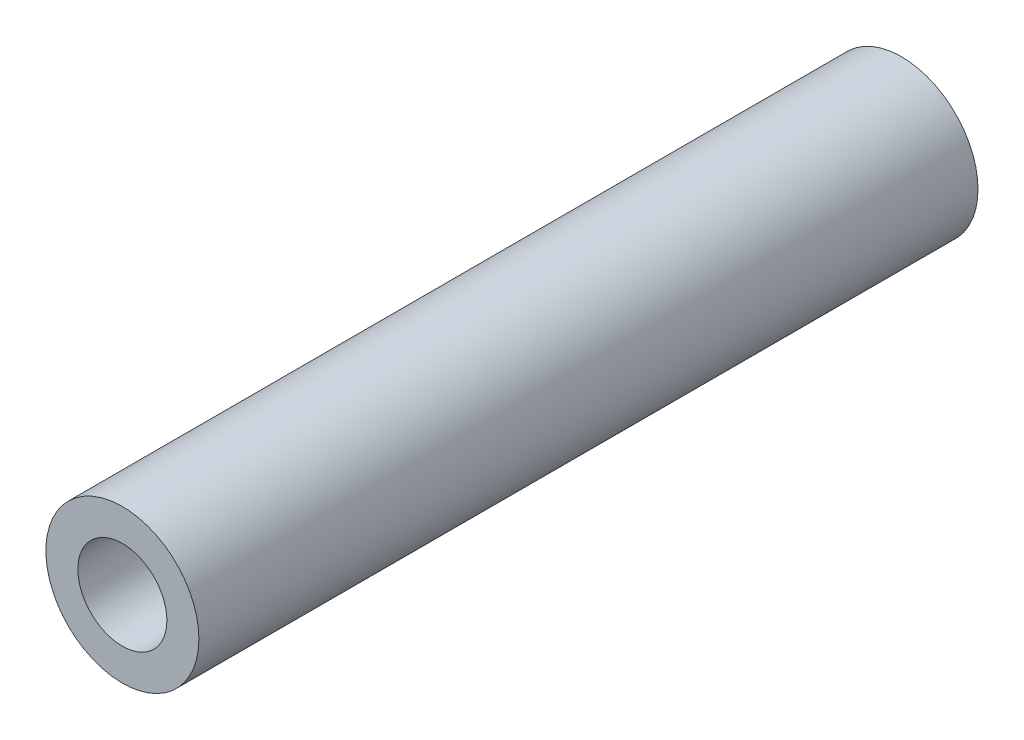
SolidWorks part; units mm, degrees
ref_plane "前视基准面" through (0, 0, 0) normal (0, 0, 1) x (1, 0, 0)
ref_plane "上视基准面" through (0, 0, 0) normal (0, 1, 0) x (1, 0, 0)
ref_plane "右视基准面" through (0, 0, 0) normal (1, 0, 0) x (0, 0, -1)
sketch "草图1" plane through (0, 0, 0) normal (0, 0, 1) x (1, 0, 0)
  circle A0 centre (0, 0) radius 2.75
  circle A1 centre (0, 0) radius 1.6
  dimension "D1" = 5.5
  dimension "D2" = 3.2
extrude "凸台-拉伸1" add sketch "草图1" along normal blind 28
